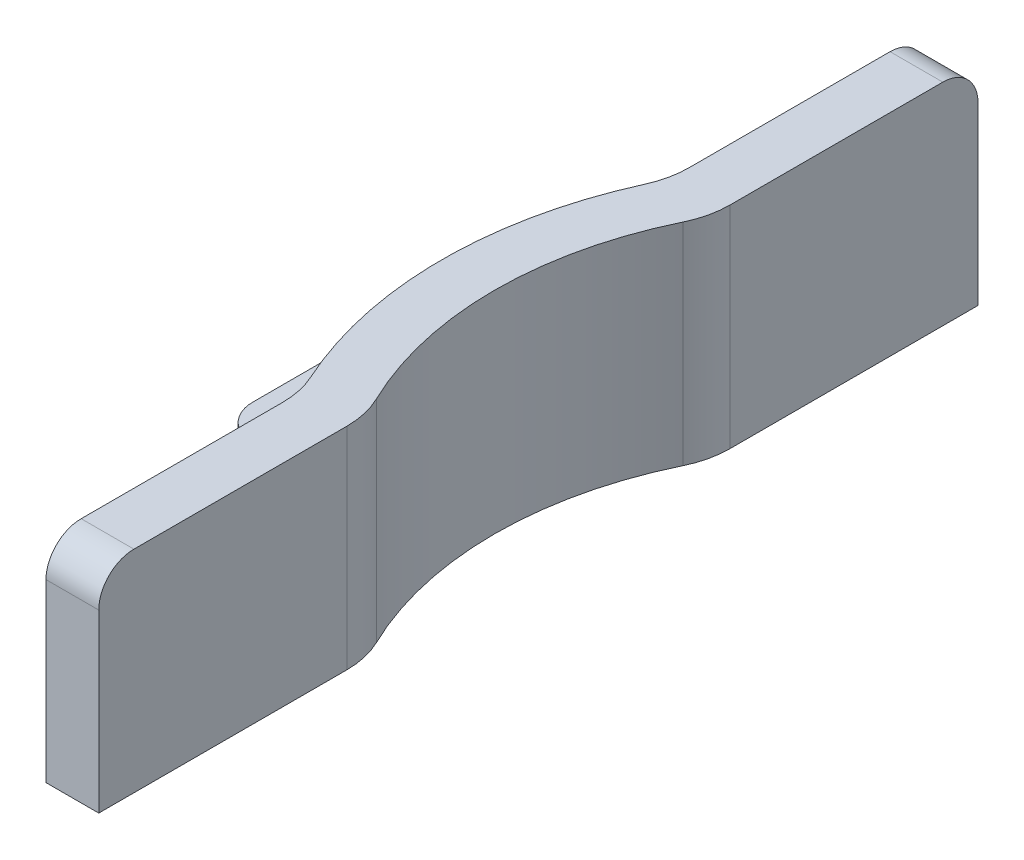
SolidWorks part; units mm, degrees
ref_plane "Front Plane" through (0, 0, 0) normal (0, 0, 1) x (1, 0, 0)
ref_plane "Top Plane" through (0, 0, 0) normal (0, 1, 0) x (1, 0, 0)
ref_plane "Right Plane" through (0, 0, 0) normal (1, 0, 0) x (0, 0, -1)
sketch "Sketch1" plane through (0, 0, 0) normal (0, 1, 0) x (1, 0, 0)
  line L1 (-20.5, 25) -> (-17.5, 25)
  line L2 (-20.5, 25) -> (-20.5, -25)
  line L3 (-20.5, -25) -> (-17.5, -25)
  line L4 (-17.5, 25) -> (-17.5, -25)
  line L5 (-20.5, 25) -> (-17.5, -25) construction
  line L6 (-20.5, -25) -> (-17.5, 25) construction
  circle A0 centre (0, 0) radius 20
  circle A1 centre (0, 0) radius 23
  point P4 (-19, 0)
  point P9 (-14.5807, 1.4993)
  point P10 (-16.505, 0)
  dimension "D1" = 40
  dimension "D2" = 3
  dimension "D3" = 50
  dimension "D4" = 3
  dimension "D5" = 19
extrude "Boss-Extrude2" add sketch "Sketch1" along normal blind 12 contours A1 L4 L1 L2 | L4 A1 L2 A0 | L2 A1 | A1 L2 L3 L4
fillet "Fillet2" radius 5 4 edges at (-20.5, 6, 10.4283) (-20.5, 6, -10.4283) (-17.5, 6, -9.6825) (-17.5, 6, 9.6825)
fillet "Fillet3" radius 2 2 edges at (-19, 12, -25) (-19, 12, 25)
sketch "Sketch2" plane through (0, 0, 0) normal (0, 1, 0) x (1, 0, 0)
  line L1 (-22.3611, 5.3834) -> (-30.3611, 5.3834)
  line L2 (-22.3611, 5.3834) -> (-22.3611, -5.3834)
  line L3 (-22.3611, -5.3834) -> (-30.3611, -5.3834)
  line L4 (-30.3611, 5.3834) -> (-30.3611, -5.3834)
  line L5 (-22.3611, 5.3834) -> (-30.3611, -5.3834) construction
  line L6 (-22.3611, -5.3834) -> (-30.3611, 5.3834) construction
  arc A0 (-20.9464, 9.4998) -> (-20.9464, -9.4998) centre (0, 0) ccw construction
  circle A1 centre (-26.3611, 0) radius 1.5
  point P0 (-26.3611, 0)
  point P5 (0, 0)
  point P9 (-26.7279, 0)
  point P13 (0, 0)
  point P14 (-26.6801, 0)
  point P15 (-26.9282, 0)
  dimension "D1" = 3
  dimension "D2" = 8
  dimension "D3" = 4
extrude "Boss-Extrude3" add sketch "Sketch2" along normal blind 3
fillet "Fillet4" radius 2 5 edges at (-23, 3, 0) (-22.3611, 1.5, 5.3834) (-30.3611, 1.5, 5.3834) (-30.3611, 1.5, -5.3834) (-22.3611, 1.5, -5.3834)
